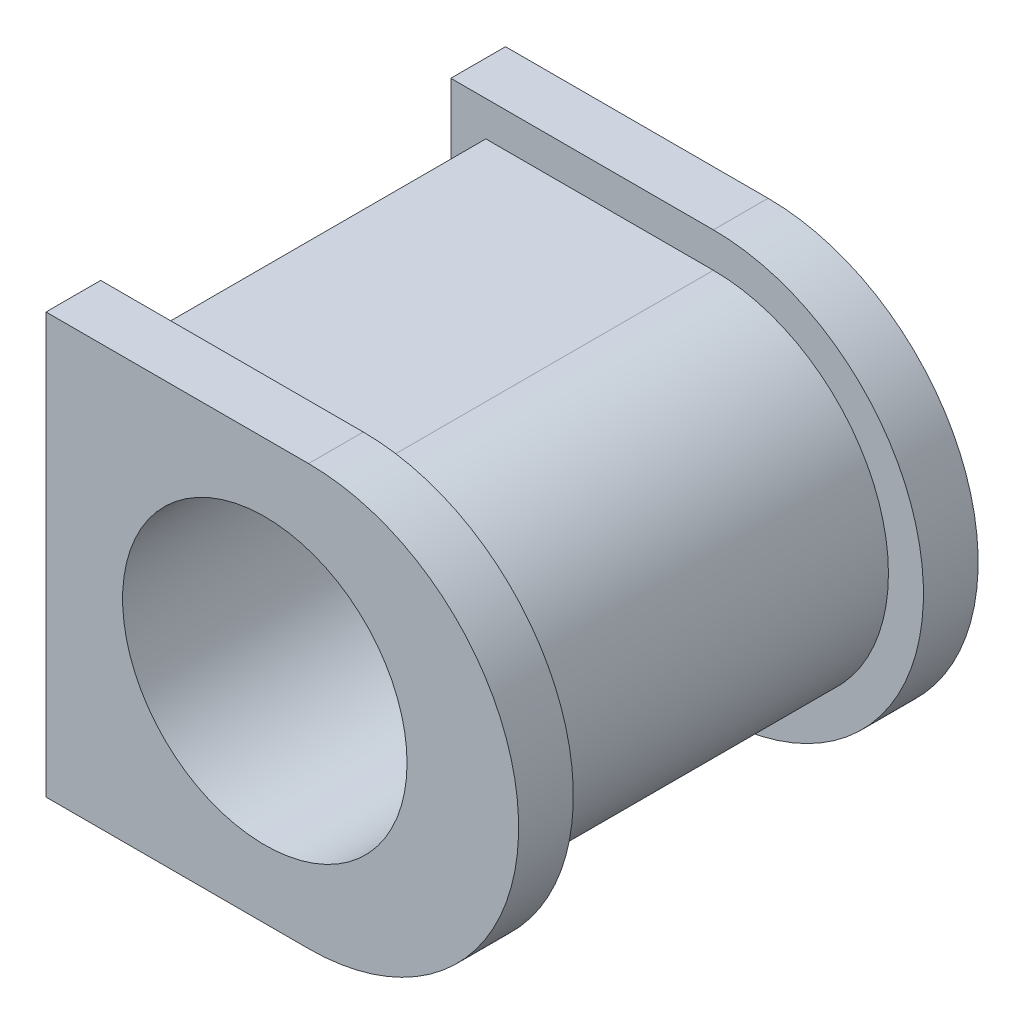
SolidWorks part; units mm, degrees
ref_plane "Front Plane" through (0, 0, 0) normal (0, 0, 1) x (1, 0, 0)
ref_plane "Top Plane" through (0, 0, 0) normal (0, 1, 0) x (1, 0, 0)
ref_plane "Right Plane" through (0, 0, 0) normal (1, 0, 0) x (0, 0, -1)
sketch "Sketch1" plane through (0, 0, 0) normal (0, 0, 1) x (1, 0, 0)
  line L0 (0, -40) -> (0, 40)
  line L1 (0, 40) -> (52, 40)
  line L2 (0, 0) -> (84.9855, 0) construction
  line L3 (0, -40) -> (52, -40)
  arc A0 (52, 40) -> (52, -40) centre (52, 0) cw
  point P8 (0, 0)
  dimension "D1" = 80
  dimension "D2" = 52
extrude "Boss-Extrude1" add sketch "Sketch1" along normal blind 80
sketch "Sketch2" plane through (0, 0, 80) normal (0, 0, 1) x (1, 0, 0)
  line L0 (-8, 48) -> (-8, -48)
  line L1 (-8, -48) -> (52, -48)
  line L2 (-8, 48) -> (52, 48)
  line L3 (52, 48) -> (52, -48) construction
  line L4 (52, 40) -> (52, -40) construction
  arc A1 (52, 48) -> (52, -48) centre (52, 0) cw
  point P2 (-8, 0)
  point P3 (52, 0)
  dimension "D1" = 96
  dimension "D2" = 60
extrude "Boss-Extrude2" add sketch "Sketch2" along normal blind 12.5
ref_plane "Plane1" through (0, 0, 40) normal (0, 0, -1) x (-1, 0, 0)
mirror "Mirror1" about plane through (0, 0, 40) normal (0, 0, -1) of bodies 102
sketch "Sketch3" plane through (0, 0, 92.5) normal (0, 0, 1) x (1, 0, 0)
  line L0 (42, 48) -> (42, -48) construction
  line L1 (52, 48) -> (-8, 48) construction
  line L2 (-8, -48) -> (52, -48) construction
  line L3 (-8, 0) -> (42, 0) construction
  line L4 (-8, 48) -> (-8, -48) construction
  dimension "D1" = 50
hole_wizard "Ø1.0mm Dowel Hole1" positions "3DSketch1" profile "Sketch4" hole size "Ø1.0" standard "ANSI Metric" end condition through all
sketch3d "3DSketch1"
  point P0 (42, 0, 92.5)
sketch "Sketch4" plane through (42, 0, 92.5) normal (1, 0, 0) x (0, -1, 0)
  line L0 (0, 0) -> (0, 105)
  line L1 (0, 105) -> (32.5, 105)
  line L2 (32.5, 105) -> (32.5, 0)
  line L5 (32.5, 0) -> (0, 0)
  line L11 (0, -6.35) -> (0, 107.95) construction
  dimension "Thru Hole Dia." = 65
  dimension "Thru Hole Depth" = 105
